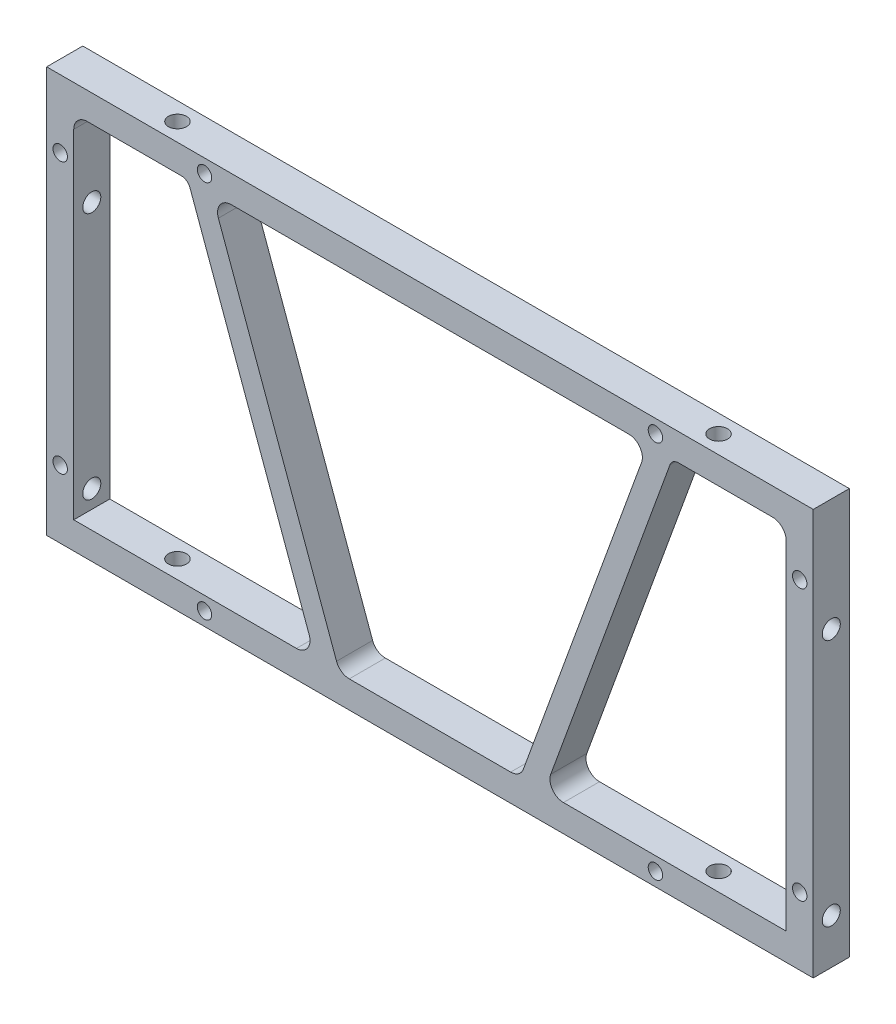
SolidWorks part; units mm, degrees
material "6061 合金"
ref_plane "前视基准面" through (0, 0, 0) normal (0, 0, 1) x (1, 0, 0)
ref_plane "上视基准面" through (0, 0, 0) normal (0, 1, 0) x (1, 0, 0)
ref_plane "右视基准面" through (0, 0, 0) normal (1, 0, 0) x (0, 0, -1)
sketch "草图1" plane through (0, 0, 0) normal (0, 0, 1) x (1, 0, 0)
  line L1 (-79, 39) -> (79, 39)
  line L2 (-79, 39) -> (-79, -39)
  line L3 (-79, -39) -> (79, -39)
  line L4 (79, 39) -> (79, -39)
  line L5 (-79, 39) -> (79, -39) construction
  line L6 (-79, -39) -> (79, 39) construction
  line L7 (-85, 45) -> (85, 45)
  line L8 (-85, 45) -> (-85, -45)
  line L9 (-85, -45) -> (85, -45)
  line L10 (85, 45) -> (85, -45)
  line L11 (-85, 45) -> (85, -45) construction
  line L12 (-85, -45) -> (85, 45) construction
  point P0 (0, 0)
  point P6 (0, 0)
  dimension "D1" = 78
  dimension "D2" = 6
  dimension "D3" = 6
  dimension "D4" = 170
extrude "凸台-拉伸1" add sketch "草图1" along normal blind 8
sketch "草图2" plane through (-85, 0, 0) normal (-1, 0, 0) x (0, 0, 1)
  line L0 (0, 0) -> (19.1533, 0) construction
  line L1 (4, 45) -> (4, -45) construction
  line L2 (8, 45) -> (0, 45) construction
  line L3 (8, -45) -> (0, -45) construction
  circle A0 centre (4, 20) radius 2
  circle A1 centre (4, -35) radius 2
  dimension "D1" = 4
  dimension "D2" = 55
  dimension "D3" = 10
extrude "切除-拉伸1" cut sketch "草图2" against normal through all
fillet "圆角1" [suppressed] radius 2
sketch "草图3" plane through (0, 45, 0) normal (0, 1, 0) x (1, 0, 0)
  line L0 (0, 0) -> (0, -49.2141) construction
  line L1 (-85, -4) -> (85, -4) construction
  line L2 (-85, -8) -> (-85, 0) construction
  line L3 (85, -8) -> (85, 0) construction
  circle A0 centre (-60, -4) radius 2
  circle A1 centre (60, -4) radius 2
  dimension "D1" = 4
  dimension "D2" = 120
extrude "切除-拉伸2" cut sketch "草图3" against normal through all
sketch "草图4" plane through (0, 0, 0) normal (0, 0, -1) x (-1, 0, 0)
  line L0 (0, 45) -> (0, -45) construction
  line L1 (-85, 45) -> (85, 45) construction
  line L2 (85, -45) -> (-85, -45) construction
  line L3 (-92.4229, 0) -> (97.1707, 0) construction
  line L4 (85, 45) -> (85, -45) construction
  line L5 (-75.0683, -42) -> (74.6285, -42) construction
  circle A0 centre (-82, 30) radius 1.6
  circle A1 centre (-82, -30) radius 1.6
  circle A2 centre (82, 30) radius 1.6
  circle A3 centre (82, -30) radius 1.6
  circle A4 centre (-50, 42) radius 1.6
  circle A5 centre (50, 42) radius 1.6
  circle A6 centre (-50, -42) radius 1.6
  circle A7 centre (50, -42) radius 1.6
  dimension "D1" = 3.2
  dimension "D2" = 60
  dimension "D3" = 3
  dimension "D4" = 3
  dimension "D5" = 3.2
  dimension "D6" = 100
extrude "切除-拉伸3" cut sketch "草图4" against normal through all and the other way through all
sketch "草图5" plane through (0, 0, 0) normal (0, 0, -1) x (-1, 0, 0)
  line L5 (0, 51.8081) -> (0, -58.2723) construction
  line L6 (-53.7106, 39) -> (-25.3209, -39)
  line L7 (-79, 39) -> (79, 39) construction
  line L8 (79, -39) -> (-79, -39) construction
  line L9 (-25.3209, -39) -> (-20, -39)
  line L10 (-20, -39) -> (-48.3897, 39)
  line L11 (-48.3897, 39) -> (-53.7106, 39)
  line L12 (53.7106, 39) -> (48.3897, 39)
  line L13 (48.3897, 39) -> (20, -39)
  line L14 (20, -39) -> (25.3209, -39)
  line L15 (25.3209, -39) -> (53.7106, 39)
  dimension "D1" = 40
  dimension "D2" = 5
  dimension "D3" = 70
extrude "凸台-拉伸2" add sketch "草图5" against normal up to surface (8 mm away) up to face at (48.4, 42, 8)
fillet "圆角2" radius 3 8 edges at (-79, 39, 4) (79, 39, 4) (-20, -39, 4) (20, -39, 4) (-25.3209, -39, 4) (25.3209, -39, 4) (-48.3897, 39, 4) (48.3897, 39, 4)
fillet "圆角3" radius 2 2 edges at (-53.7106, 39, 4) (53.7106, 39, 4)
